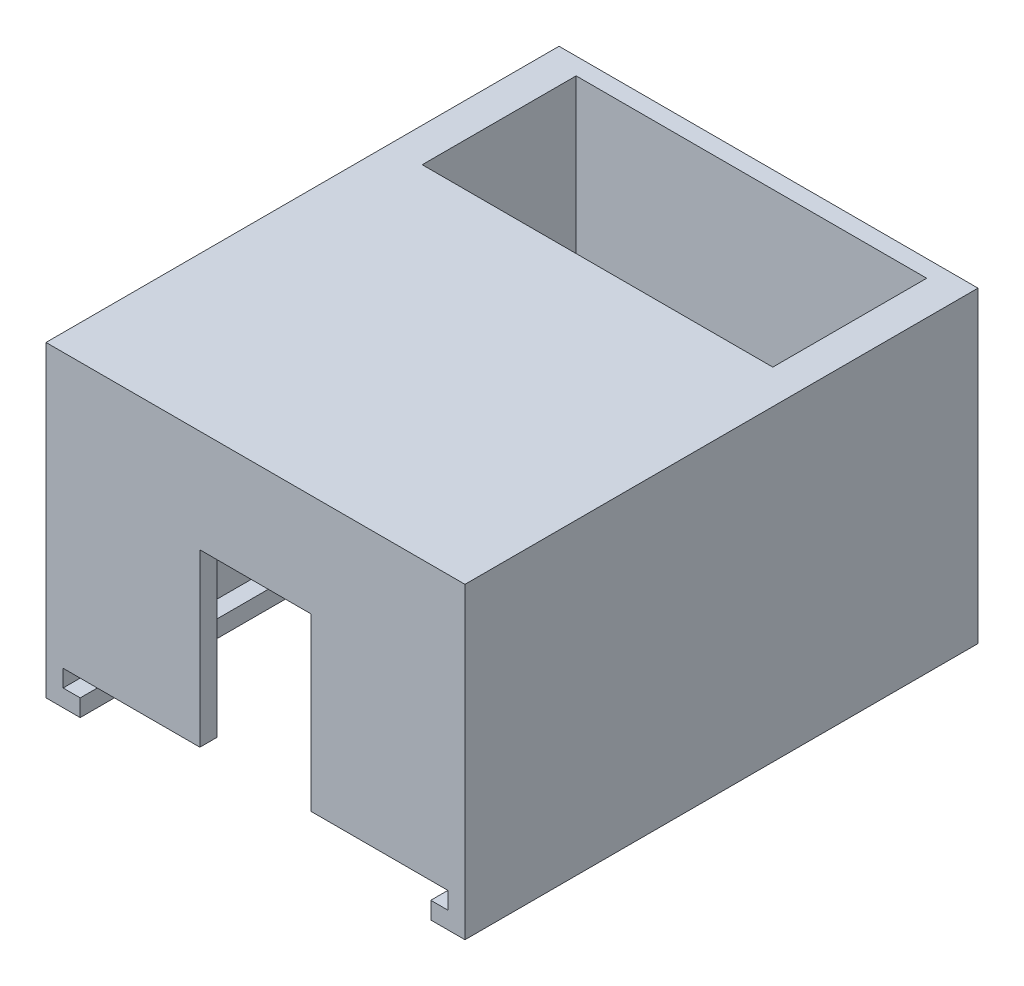
SolidWorks part; units mm, degrees
ref_plane "Plan de face" through (0, 0, 0) normal (0, 0, 1) x (1, 0, 0)
ref_plane "Plan de dessus" through (0, 0, 0) normal (0, 1, 0) x (1, 0, 0)
ref_plane "Plan de droite" through (0, 0, 0) normal (1, 0, 0) x (0, 0, -1)
sketch "Esquisse1" plane through (0, 0, 0) normal (0, 0, 1) x (1, 0, 0)
  line L1 (0, 0) -> (24.5, 0)
  line L2 (0, 0) -> (0, 18)
  line L3 (0, 18) -> (24.5, 18)
  line L4 (24.5, 0) -> (24.5, 18)
  dimension "D1" = 24.5
  dimension "D2" = 18
extrude "Boss.-Extru.3" add sketch "Esquisse1" along normal blind 30
sketch "Esquisse4" plane through (0, 0, 30) normal (0, 0, 1) x (1, 0, 0)
  line L0 (2, 17) -> (2, 0)
  line L1 (0, 0) -> (24.5, 0) construction
  line L2 (2, 17) -> (22.5, 17)
  line L3 (22.5, 17) -> (22.5, 0)
  line L4 (0, 18) -> (0, 0) construction
  line L5 (24.5, 18) -> (0, 18) construction
  line L6 (24.5, 0) -> (24.5, 18) construction
  dimension "D1" = 2
  dimension "D2" = 1
  dimension "D3" = 2
extrude "Enlèv. mat.-Extru.1" cut sketch "Esquisse4" against normal blind 29 and the other way through all
sketch "Esquisse5" plane through (2, 0, 0) normal (1, 0, 0) x (0, 0, -1)
  line L0 (-1, 1) -> (-30, 1)
  line L2 (-1, 0) -> (-1, 17) construction
  line L3 (-30, 0) -> (-30, 17) construction
  line L5 (-30, 2) -> (-2, 2)
  line L6 (-30, 0) -> (-1, 0) construction
  line L7 (-30, 1) -> (-30, 2)
  line L8 (-2, 2) -> (-1, 2)
  line L9 (-1, 2) -> (-1, 1)
  dimension "D1" = 1
  dimension "D2" = 1
extrude "Enlèv. mat.-Extru.2" cut sketch "Esquisse5" against normal blind 1
sketch "Esquisse6" plane through (22.5, 0, 0) normal (-1, 0, 0) x (0, 0, 1)
  line L0 (1, 1) -> (30, 1)
  line L1 (1, 17) -> (1, 0) construction
  line L2 (30, 17) -> (30, 0) construction
  line L3 (30, 1) -> (30, 2)
  line L4 (30, 2) -> (1, 2)
  line L5 (1, 2) -> (1, 1)
  line L6 (30, 0) -> (1, 0) construction
  dimension "D1" = 1
  dimension "D2" = 1
extrude "Enlèv. mat.-Extru.3" cut sketch "Esquisse6" against normal blind 1
sketch "Esquisse7" plane through (0, 0, 30) normal (0, 0, 1) x (1, 0, 0)
  line L1 (2, 17) -> (22.5, 17)
  line L2 (2, 17) -> (2, 2)
  line L3 (2, 2) -> (22.5, 2)
  line L4 (22.5, 17) -> (22.5, 2)
extrude "Boss.-Extru.4" add sketch "Esquisse7" against normal blind 1
sketch "Esquisse8" plane through (0, 0, 30) normal (0, 0, 1) x (1, 0, 0)
  line L0 (9, 2) -> (9, 12)
  line L1 (1, 2) -> (23.5, 2) construction
  line L2 (9, 12) -> (15.5, 12)
  line L3 (15.5, 12) -> (15.5, 2)
  line L4 (9, 2) -> (15.5, 2)
  dimension "D1" = 7
  dimension "D2" = 7
  dimension "D3" = 10
extrude "Enlèv. mat.-Extru.4" cut sketch "Esquisse8" against normal blind 1
sketch "Esquisse10" plane through (0, 17, 0) normal (0, -1, 0) x (-1, 0, 0)
  line L0 (-22.5, -29) -> (-22.5, -1) construction
  line L1 (-2, -1) -> (-22.5, -1)
  line L2 (-2, -1) -> (-2, -10)
  line L3 (-2, -10) -> (-22.5, -10)
  line L4 (-22.5, -1) -> (-22.5, -10)
  dimension "D1" = 9
extrude "Enlèv. mat.-Extru.5" cut sketch "Esquisse10" against normal through all
